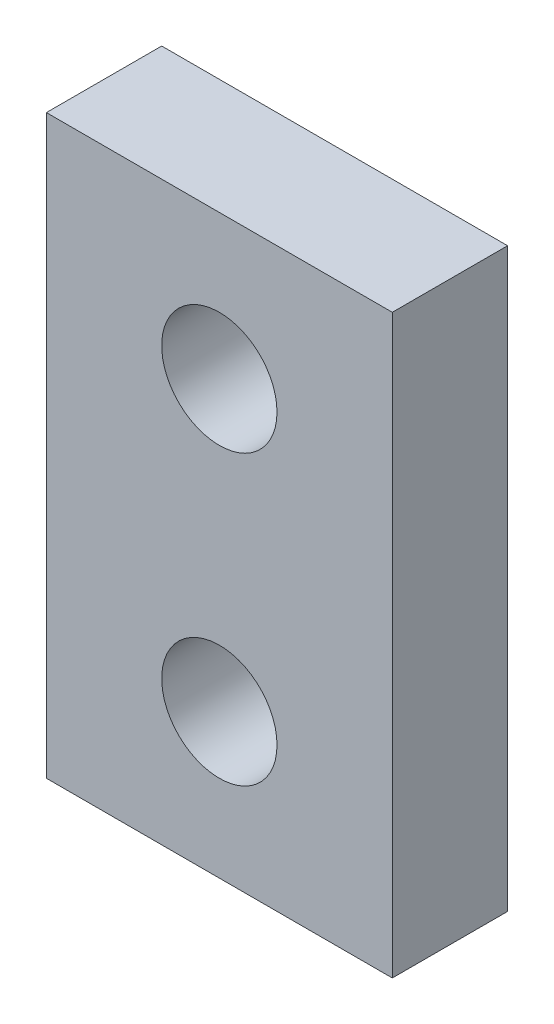
SolidWorks part; units mm, degrees
ref_plane "Alzado" through (0, 0, 0) normal (0, 0, 1) x (1, 0, 0)
ref_plane "Planta" through (0, 0, 0) normal (0, 1, 0) x (1, 0, 0)
ref_plane "Vista lateral" through (0, 0, 0) normal (1, 0, 0) x (0, 0, -1)
sketch "Croquis1" plane through (0, 0, 0) normal (0, 0, 1) x (1, 0, 0)
  line L1 (-15, -25) -> (15, -25)
  line L2 (-15, -25) -> (-15, 25)
  line L3 (-15, 25) -> (15, 25)
  line L4 (15, -25) -> (15, 25)
  line L5 (-15, -25) -> (15, 25) construction
  line L6 (-15, 25) -> (15, -25) construction
  circle A0 centre (0, 12.5) radius 5
  circle A1 centre (0, -12.5) radius 5
  point P0 (0, 0)
  point P10 (0, 25)
  point P11 (0, 0)
  point P12 (0, -25)
  dimension "D3" = 10
  dimension "D4" = 10
  dimension "D6" = 12.5
  dimension "D1" = 30
  dimension "D2" = 50
  dimension "D5" = 25
extrude "Saliente-Extruir1" add sketch "Croquis1" along normal blind 10
